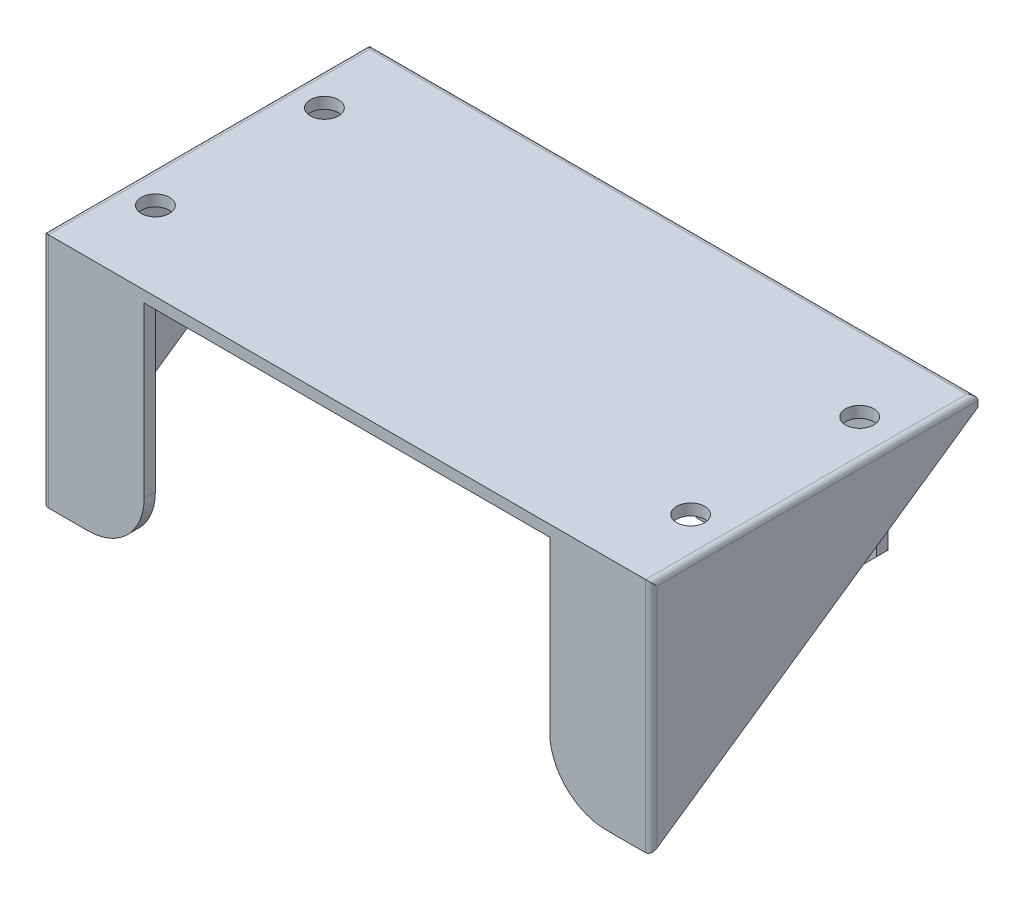
SolidWorks part; units mm, degrees
ref_plane "前视基准面" through (0, 0, 0) normal (0, 0, 1) x (1, 0, 0)
ref_plane "上视基准面" through (0, 0, 0) normal (0, 1, 0) x (1, 0, 0)
ref_plane "右视基准面" through (0, 0, 0) normal (1, 0, 0) x (0, 0, -1)
sketch "草图1" plane through (0, 0, 0) normal (0, 1, 0) x (1, 0, 0)
  line L0 (0, 0) -> (-54, 0)
  line L1 (-54, 0) -> (-54, 29)
  line L2 (-54, 29) -> (0, 29)
  line L3 (0, 29) -> (0, 0)
  dimension "D1" = 54
  dimension "D2" = 29
extrude "凸台-拉伸1" add sketch "草图1" along normal blind 1
sketch "草图2" plane through (-54, 0, 0) normal (-1, 0, 0) x (0, 0, 1)
  line L0 (-29, 0) -> (0, 0)
  line L1 (0, 0) -> (0, -20)
  line L2 (0, -20) -> (-29, 0)
  dimension "D1" = 20
extrude "凸台-拉伸2" add sketch "草图2" against normal blind 1
sketch "草图3" plane through (0, 0, 0) normal (1, 0, 0) x (0, 0, -1)
  line L0 (0, 0) -> (0, -20)
  line L1 (0, -20) -> (29, 0)
  line L2 (29, 0) -> (0, 0)
extrude "凸台-拉伸3" add sketch "草图3" against normal blind 1
sketch "草图4" plane through (-1, 0, 0) normal (-1, 0, 0) x (0, 0, 1)
  line L0 (0, 0) -> (0, -20)
  line L1 (0, -20) -> (-1, -20)
  line L2 (-1, -20) -> (-1, 0)
  line L3 (-1, 0) -> (0, 0)
  dimension "D1" = 1
extrude "凸台-拉伸4" add sketch "草图4" along normal blind 8
sketch "草图5" plane through (-53, 0, 0) normal (1, 0, 0) x (0, 0, -1)
  line L0 (0, -20) -> (1, -20)
  line L1 (1, -20) -> (1, 0)
  line L2 (1, 0) -> (0, 0)
  line L3 (0, 0) -> (0, -20)
extrude "凸台-拉伸5" add sketch "草图5" along normal blind 8
sketch "草图6" plane through (0, 0, 0) normal (0, -1, 0) x (1, 0, 0)
  line L0 (-8, -29) -> (-8, -28)
  line L1 (-1, -29) -> (-53, -29) construction
  line L2 (-8, -28) -> (-29, -28)
  line L3 (-29, -28) -> (-29, -29)
  line L4 (-29, -29) -> (-8, -29)
  line L5 (-1, -29) -> (-1, -1) construction
  dimension "D1" = 1
  dimension "D2" = 7
  dimension "D3" = 21
extrude "凸台-拉伸6" add sketch "草图6" along normal blind 20
hole_wizard "M3 螺纹孔1" positions "草图7" profile "草图8" tap size "M3" standard "IS" end condition up to next
sketch "草图7" plane through (0, 0, -29) normal (0, 0, -1) x (-1, 0, 0)
  line L0 (8, -20) -> (8, 0) construction
  line L2 (0, 1) -> (54, 1) construction
  point P0 (18, -10)
  point P9 (15.6867, -20)
  point P16 (-10.415, 6.573)
  dimension "D1" = 10
  dimension "D2" = 11
sketch "草图8" plane through (-18, -10, -29) normal (1, 0, 0) x (0, 1, 0)
  line L0 (0, 0) -> (0, 1)
  line L1 (0, 1) -> (1.25, 1)
  line L2 (1.25, 1) -> (1.25, 0)
  line L5 (1.25, 0) -> (0, 0)
  line L11 (0, -6.35) -> (0, 107.95) construction
  dimension "通孔螺纹孔钻头直径" = 2.5
  dimension "通孔螺纹孔钻头深度" = 1
cosmetic thread "孔螺蚊线1" parameters "D2"=3
chamfer "倒角1" distance 5 2 edges at (-8, -20, -28.5) (-29, -20, -28.5)
fillet "圆角1" radius 0.5 5 edges at (0, 1, -14.5) (0, -9.5, 0) (-54, -9.5, 0) (-54, 1, -14.5) (-27, 1, -29)
fillet "圆角2" radius 5 2 edges at (-9, -20, -0.5) (-45, -20, -0.5)
hole_wizard "M3 螺纹孔2" positions "草图9" profile "草图10" tap size "M3" standard "IS" end condition up to next
sketch "草图9" plane through (0, 1, 0) normal (0, 1, 0) x (1, 0, 0)
  line L0 (-54, 0.5) -> (-54, 29) construction
  line L1 (-0.5, 0) -> (-0.5, 28.5) construction
  line L2 (-54, 29) -> (0, 29) construction
  point P0 (-51, 22)
  point P2 (-51, 7)
  point P4 (-3.5, 7)
  point P6 (-3.5, 22)
  dimension "D1" = 3
  dimension "D2" = 3
  dimension "D3" = 3
  dimension "D4" = 3
  dimension "D5" = 7
  dimension "D6" = 7
  dimension "D7" = 15
  dimension "D8" = 15
sketch "草图10" plane through (-51, 1, -22) normal (1, 0, 0) x (0, 0, 1)
  line L0 (0, 0) -> (0, 1)
  line L1 (0, 1) -> (1.25, 1)
  line L2 (1.25, 1) -> (1.25, 0)
  line L5 (1.25, 0) -> (0, 0)
  line L11 (0, -6.35) -> (0, 107.95) construction
  dimension "通孔螺纹孔钻头直径" = 2.5
  dimension "通孔螺纹孔钻头深度" = 1
cosmetic thread "孔螺蚊线2" parameters "D2"=3
cosmetic thread "孔螺蚊线3" parameters "D2"=3
cosmetic thread "孔螺蚊线4" parameters "D2"=3
cosmetic thread "孔螺蚊线5" parameters "D2"=3
